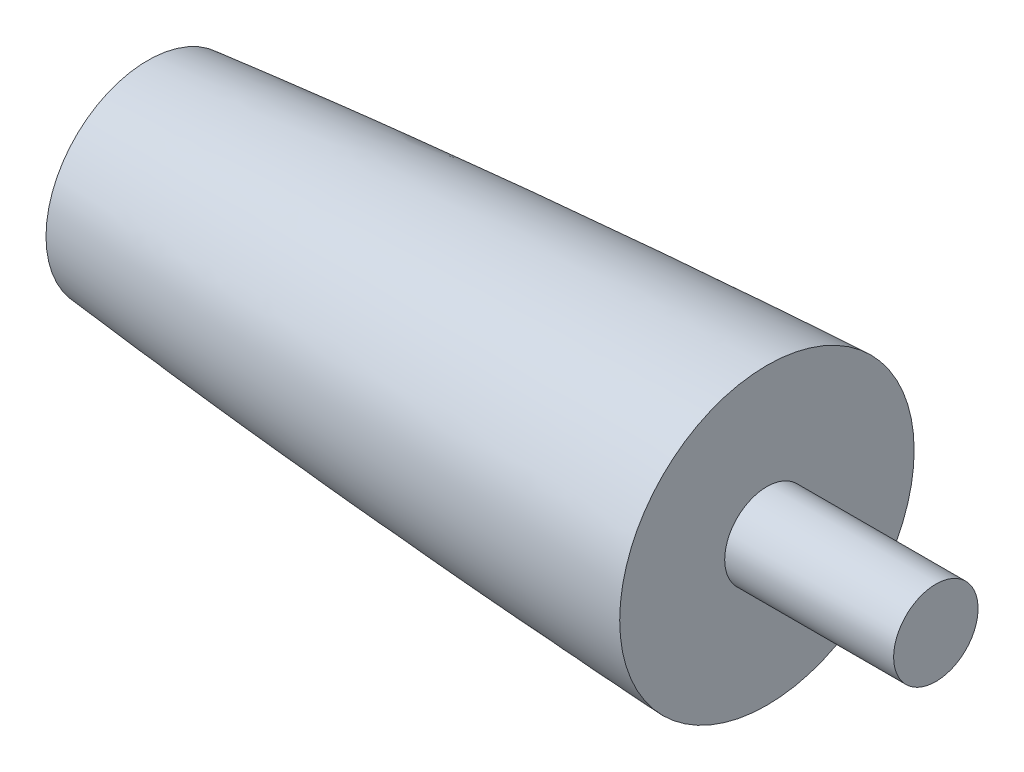
SolidWorks part; units mm, degrees
ref_plane "Front Plane" through (0, 0, 0) normal (0, 0, 1) x (1, 0, 0)
ref_plane "Top Plane" through (0, 0, 0) normal (0, 1, 0) x (1, 0, 0)
ref_plane "Right Plane" through (0, 0, 0) normal (1, 0, 0) x (0, 0, -1)
sketch "Sketch1" plane through (0, 0, 0) normal (0, 1, 0) x (1, 0, 0)
  line L0 (186.2, 30.5942) -> (186.2, 0)
  line L1 (186.2, 0) -> (423.2, 0)
  line L2 (423.2, 0) -> (423.2, 12.7)
  line L3 (423.2, 12.7) -> (372.4, 12.7)
  line L4 (372.4, 12.7) -> (372.4, 44.2733)
  spline S0 degree 4 poles (167.7526, 28.6744) (168.0659, 28.7079) (168.6708, 28.7727) (169.6836, 28.882) (171.7184, 29.0969) (173.2895, 29.2653) (176.8672, 29.6377) (179.17, 29.88) (184.53, 30.4259) (186.785, 30.6538) (191.9188, 31.1664) (196.1245, 31.5784) (201.8409, 32.1312) (207.8937, 32.7017) (214.2054, 33.2858) (220.3684, 33.8426) (226.6222, 34.3966) (232.8228, 34.9334) (239.0572, 35.4621) (245.2727, 35.9774) (251.501, 36.4828) (259.1272, 37.088) (268.3177, 37.7966) (279.059, 38.5948) (289.8135, 39.3588) (299.1501, 39.9971) (306.9504, 40.5135) (313.1597, 40.9153) (319.4324, 41.3106) (325.595, 41.6909) (331.9449, 42.0709) (337.9854, 42.4262) (344.538, 42.7977) (350.248, 43.118) (357.3494, 43.4983) (362.1482, 43.755) (370.2189, 44.165) (373.3789, 44.3228) (379.8398, 44.6389) (383.2011, 44.7975) (387.1054, 44.9813) (389.1954, 45.0766) (390.4621, 45.1349) (391.0241, 45.1604) knots 0 0 0 0 0 0.005205 0.01041 0.02082 0.031231 0.041641 0.062209 0.082777 0.096722 0.110666 0.138556 0.166445 0.194334 0.222224 0.250113 0.278003 0.305892 0.333782 0.361671 0.38956 0.41745 0.470511 0.52629 0.582069 0.609958 0.637848 0.665737 0.693627 0.721516 0.749405 0.777295 0.805184 0.833074 0.860963 0.888853 0.916742 0.937557 0.958371 0.979186 0.989593 1 1 1 1 1 construction
  spline S1 degree 4 poles (186.2, 30.5942) (186.8477, 30.6594) (188.1681, 30.7919) (191.9188, 31.1664) (196.1245, 31.5784) (201.8409, 32.1312) (207.8937, 32.7017) (214.2054, 33.2858) (220.3684, 33.8426) (226.6222, 34.3966) (232.8228, 34.9334) (239.0572, 35.4621) (245.2727, 35.9774) (251.501, 36.4828) (259.1272, 37.088) (268.3177, 37.7966) (279.059, 38.5948) (289.8135, 39.3588) (299.1501, 39.9971) (306.9504, 40.5135) (313.1597, 40.9153) (319.4324, 41.3106) (325.595, 41.6909) (331.9449, 42.0709) (337.9854, 42.4262) (344.538, 42.7977) (350.248, 43.118) (357.3494, 43.4983) (362.1482, 43.755) (368.6111, 44.0833) (371.0997, 44.2086) (372.4, 44.2733) knots 0.082777 0.082777 0.082777 0.082777 0.082777 0.096722 0.110666 0.138556 0.166445 0.194334 0.222224 0.250113 0.278003 0.305892 0.333782 0.361671 0.38956 0.41745 0.470511 0.52629 0.582069 0.609958 0.637848 0.665737 0.693627 0.721516 0.749405 0.777295 0.805184 0.833074 0.860963 0.888853 0.916742 0.916742 0.916742 0.916742 0.916742
revolve "Revolve1" add sketch "Sketch1" angle 360 about L1
sketch "Sketch2" plane through (186.2, 0, 0) normal (-1, 0, 0) x (0, 0, 1)
  circle A0 centre (0, 0) radius 12.7
extrude "Cut-Extrude1" cut sketch "Sketch2" against normal blind 50.8
